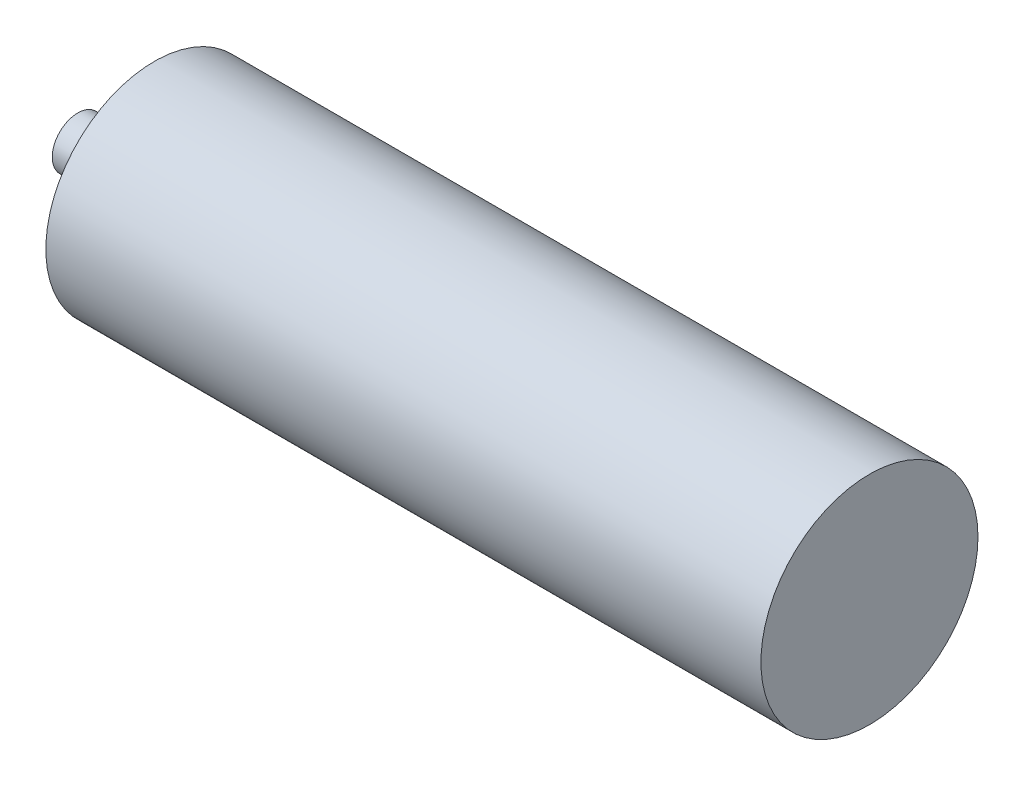
SolidWorks part; units mm, degrees
ref_plane "Front Plane" through (0, 0, 0) normal (1, 0, 0) x (0, 1, 0)
ref_plane "Top Plane" through (0, 0, 0) normal (0, 0, 1) x (0, 1, 0)
ref_plane "Right Plane" through (0, 0, 0) normal (0, 1, 0) x (-1, 0, 0)
sketch "Sketch1" plane through (0, 0, 0) normal (1, 0, 0) x (0, 1, 0)
  circle A0 centre (-10.2713, 8.8744) radius 26.9875
  dimension "D1" = 53.975
extrude "Boss-Extrude1" add sketch "Sketch1" along normal blind 177.8
sketch "Sketch4" plane through (0, 0, 0) normal (-1, 0, 0) x (0, 0, 1)
  circle A0 centre (8.8744, -10.2713) radius 6.35
  circle A1 centre (8.8744, -10.2713) radius 26.9875 construction
  dimension "D1" = 0
  dimension "D2" = 12.7
extrude "Boss-Extrude3" add sketch "Sketch4" along normal blind 19.05
